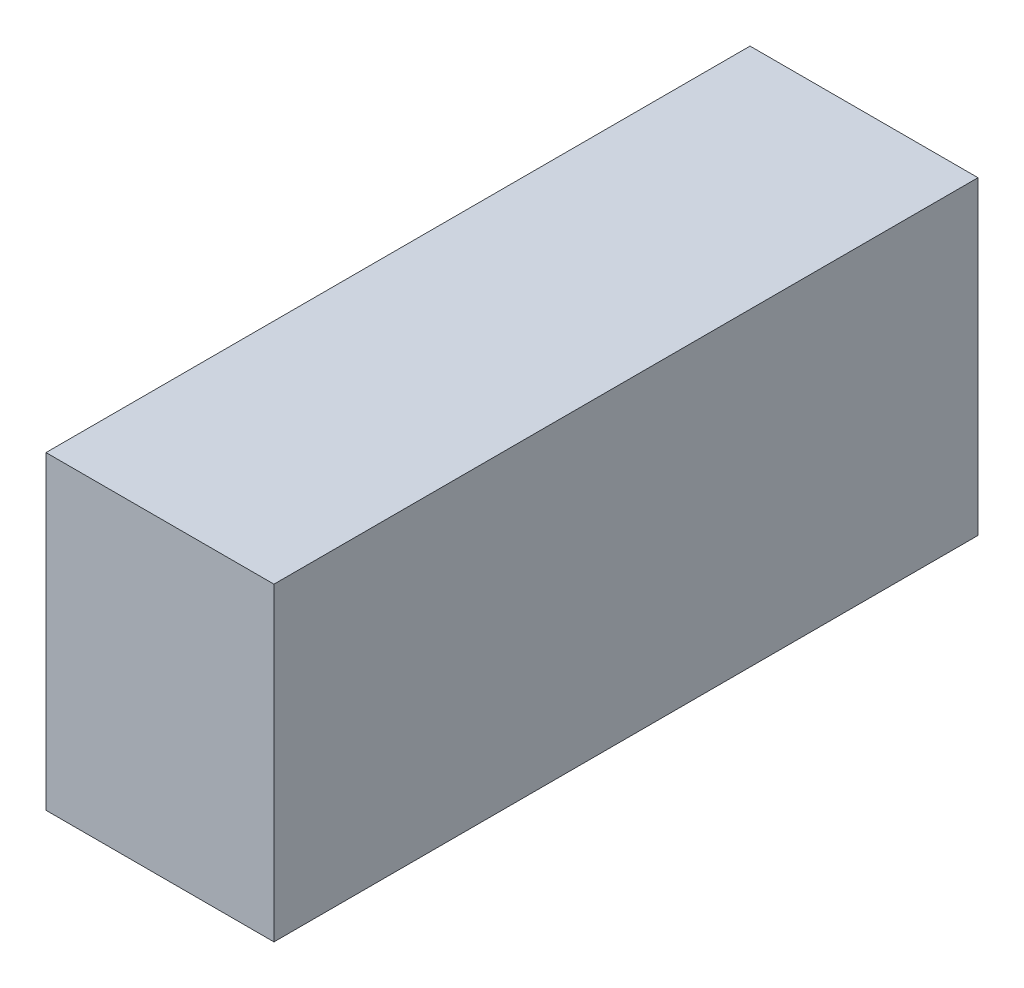
SolidWorks part; units mm, degrees
ref_plane "Front Plane" through (0, 0, 0) normal (0, 0, 1) x (1, 0, 0)
ref_plane "Top Plane" through (0, 0, 0) normal (0, 1, 0) x (1, 0, 0)
ref_plane "Right Plane" through (0, 0, 0) normal (1, 0, 0) x (0, 0, -1)
sketch "Sketch1" plane through (0, 0, 0) normal (0, 1, 0) x (1, 0, 0)
  line L1 (0, 0) -> (45.974, 0)
  line L2 (0, 0) -> (0, 141.986)
  line L3 (0, 141.986) -> (45.974, 141.986)
  line L4 (45.974, 0) -> (45.974, 141.986)
  dimension "D1" = 141.986
  dimension "D2" = 45.974
extrude "Boss-Extrude1" add sketch "Sketch1" along normal blind 62.484
